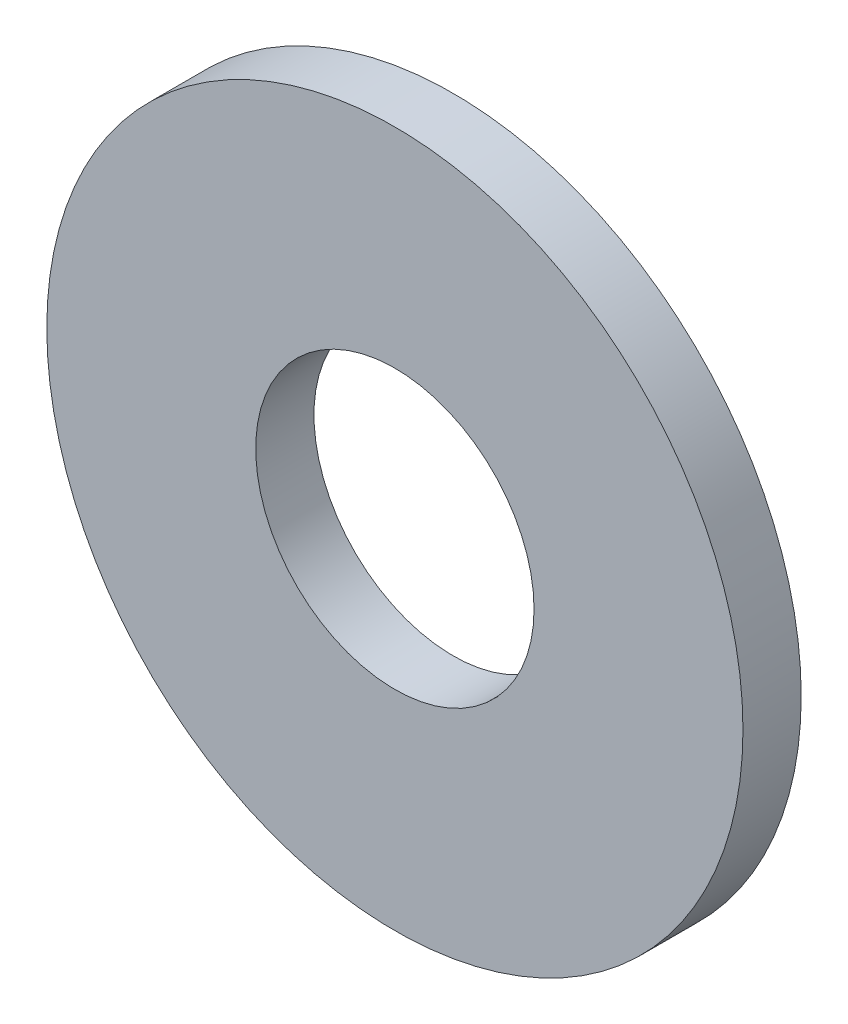
SolidWorks part; units mm, degrees
ref_plane "Front Plane" through (0, 0, 0) normal (0, 0, 1) x (1, 0, 0)
ref_plane "Top Plane" through (0, 0, 0) normal (0, 1, 0) x (1, 0, 0)
ref_plane "Right Plane" through (0, 0, 0) normal (1, 0, 0) x (0, 0, -1)
sketch "Sketch1" plane through (0, 0, 0) normal (0, 0, 1) x (1, 0, 0)
  circle A0 centre (0, 0) radius 15.1765
  circle A1 centre (0, 0) radius 37.9603
  dimension "D1" = 75.9206
  dimension "D2" = 30.353
extrude "Boss-Extrude1" add sketch "Sketch1" along normal blind 6.35
